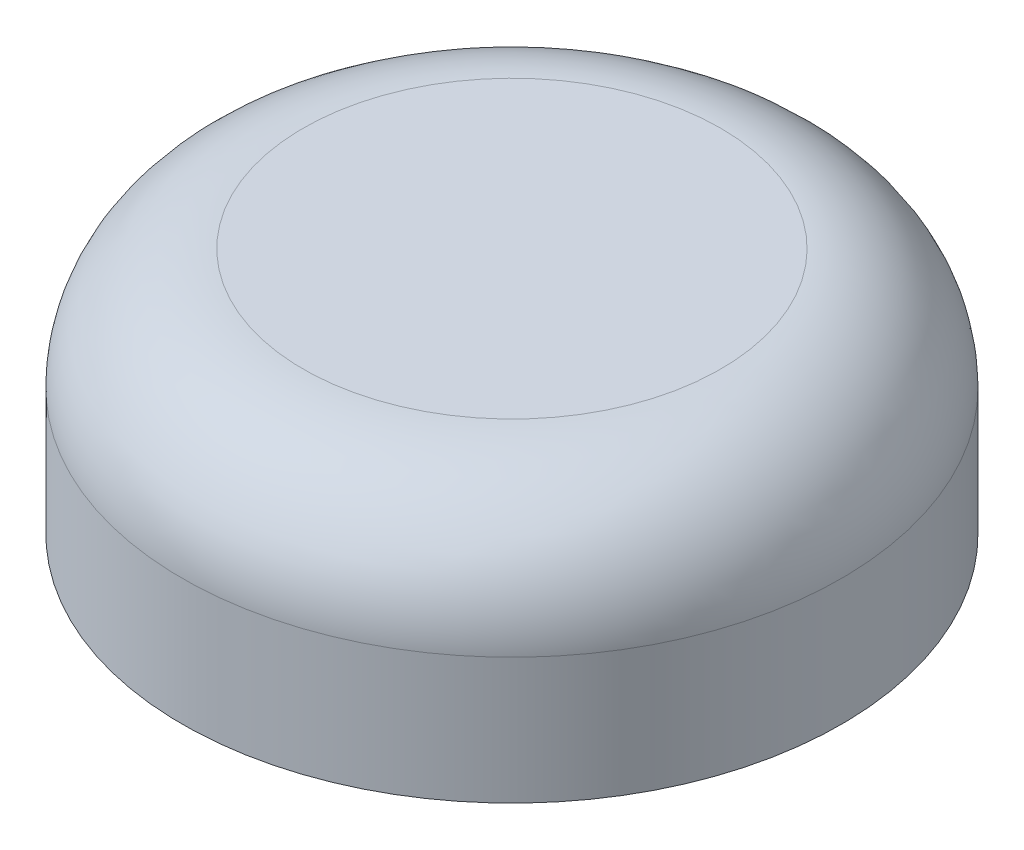
SolidWorks part; units mm, degrees
ref_plane "Front Plane" through (0, 0, 0) normal (0, 0, 1) x (1, 0, 0)
ref_plane "Top Plane" through (0, 0, 0) normal (0, 1, 0) x (1, 0, 0)
ref_plane "Right Plane" through (0, 0, 0) normal (1, 0, 0) x (0, 0, -1)
sketch "Sketch1" plane through (0, 0, 0) normal (0, 0, 1) x (1, 0, 0)
  line L0 (0, 0) -> (-24.13, 0)
  line L1 (-33.02, -8.89) -> (-33.02, -10.795)
  line L2 (-33.02, -10.795) -> (-35.56, -10.795)
  line L3 (-35.56, -10.795) -> (-35.56, -23.495)
  line L4 (-35.56, -23.495) -> (-38.1, -23.495)
  line L5 (-38.1, -23.495) -> (-38.1, -8.89)
  line L6 (0, 0) -> (0, 5.08)
  line L7 (0, 5.08) -> (-24.13, 5.08)
  arc A0 (-24.13, 0) -> (-33.02, -8.89) centre (-24.13, -8.89) ccw
  arc A1 (-24.13, 5.08) -> (-38.1, -8.89) centre (-24.13, -8.89) ccw
  dimension "D7" = 8.89
  dimension "D1" = 2.54
  dimension "D2" = 5.08
  dimension "D3" = 5.08
  dimension "D4" = 38.1
  dimension "D5" = 12.7
  dimension "D6" = 28.575
revolve "Revolve1" add sketch "Sketch1" angle 360 about L6
